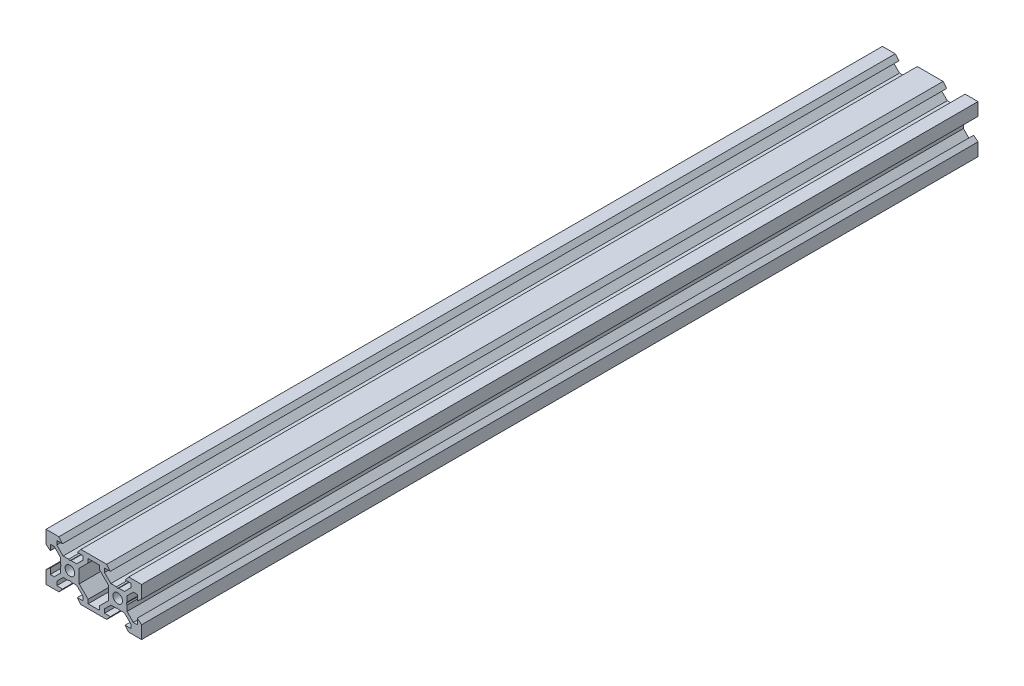
SolidWorks part; units mm, degrees
ref_plane "Front Plane" through (0, 0, 0) normal (0, 0, 1) x (1, 0, 0)
ref_plane "Top Plane" through (0, 0, 0) normal (0, 1, 0) x (1, 0, 0)
ref_plane "Right Plane" through (0, 0, 0) normal (1, 0, 0) x (0, 0, -1)
sketch "Sketch1" plane through (0, 0, 0) normal (0, 0, 1) x (1, 0, 0)
  line L0 (-5.3896, 10) -> (5.3896, 10)
  line L1 (0, 10) -> (0, 4.6104) construction
  line L2 (-6.1, -2.8393) -> (-2.3769, -6.5562)
  line L3 (5.3896, -10) -> (-5.3896, -10) construction
  line L5 (-6.1, 2.8393) -> (-6.1, -2.8393)
  line L6 (-4.5, 8.2) -> (-4.5, 6.5562)
  line L7 (2.3832, 6.5562) -> (2.3832, 8.2)
  line L9 (-6.1, 2.8393) -> (-2.3832, 6.5562)
  line L10 (-4.5, 6.5562) -> (-7.1607, 3.9)
  line L11 (-2.3832, 6.5562) -> (-2.3832, 8.2)
  line L12 (-5.3896, 10) -> (-6.9, 8.2)
  line L13 (6.1, 2.8393) -> (2.3832, 6.5562)
  line L14 (-6.9, 8.2) -> (-4.5, 8.2)
  line L15 (-16.5562, 5.5) -> (-18.2, 5.5)
  line L16 (0, 0) -> (6.1, 0) construction
  line L17 (-6.9, -8.2) -> (-4.5, -8.2)
  line L18 (-2.3769, -6.5562) -> (-2.3769, -8.2)
  line L19 (-5.3896, -10) -> (-6.9, -8.2)
  line L20 (2.3769, -6.5562) -> (2.3769, -8.2)
  line L21 (-9.4804, -3.9002) -> (-10, -3.6002)
  line L22 (-9.4804, 3.8998) -> (-10, 3.5998)
  line L23 (6.1, -2.8393) -> (2.3769, -6.5562)
  line L24 (-2.3769, -8.2) -> (2.3769, -8.2)
  line L25 (-2.3832, 8.2) -> (2.3832, 8.2)
  line L26 (-9.4804, 3.8998) -> (-7.1607, 3.9)
  line L27 (-5.3896, -10) -> (5.3896, -10)
  line L28 (-9.4804, -3.9002) -> (-7.1604, -3.9002)
  line L29 (-4.5, -6.5562) -> (-7.1607, -3.9)
  line L30 (-20, 10) -> (20, 10) construction
  line L32 (6.1, 2.8393) -> (6.1, -2.8393)
  line L33 (-4.5, -8.2) -> (-4.5, -6.5562)
  line L34 (-16.5562, -5.5) -> (-18.2, -5.5)
  line L36 (-10, 0) -> (-10, 8.2) construction
  line L37 (-20, -10) -> (-14.6104, -10) construction
  line L38 (-20, -10) -> (-20, -4.6104) construction
  line L39 (-20, 10) -> (-20, 4.6104) construction
  line L40 (-20, 10) -> (-14.6104, 10) construction
  line L41 (-20, -10) -> (-20, -4.6104)
  line L42 (-15.5, -8.2) -> (-15.5, -6.5562)
  line L43 (-20, -10) -> (-14.6104, -10)
  line L44 (7.1519, 3.8998) -> (9.4804, 3.8998)
  line L45 (-16.5562, -5.5) -> (-13.9, -2.8393)
  line L46 (-15.5, -6.5562) -> (-12.8393, -3.9)
  line L47 (-12.8393, -3.9) -> (-10.5196, -3.9002)
  line L48 (-13.9, -2.8393) -> (-13.9, -0.5196)
  line L49 (-12.8393, 3.9) -> (-10.5196, 3.8998)
  line L50 (-13.9, 0.5196) -> (-13.9, 2.8393)
  line L51 (-13.9, 0.5196) -> (-13.6, 0)
  line L52 (-13.6, 0) -> (-13.9, -0.5196)
  line L53 (-10.5196, 3.8998) -> (-10, 3.5998)
  line L54 (-10.5196, -3.9002) -> (-10, -3.6002)
  line L55 (-20, -4.6104) -> (-18.2, -3.1)
  line L56 (-14.6104, -10) -> (-13.1, -8.2)
  line L57 (-18.2, -3.1) -> (-18.2, -5.5)
  line L58 (-13.1, -8.2) -> (-15.5, -8.2)
  line L59 (-20, -10) -> (20, -10) construction
  line L60 (-20, -10) -> (-20, 10) construction
  line L61 (-13.1, 8.2) -> (-15.5, 8.2)
  line L62 (-18.2, 3.1) -> (-18.2, 5.5)
  line L63 (-14.6104, 10) -> (-13.1, 8.2)
  line L64 (-20, 4.6104) -> (-18.2, 3.1)
  line L65 (-15.5, 6.5562) -> (-12.8393, 3.9)
  line L66 (-16.5562, 5.5) -> (-13.9, 2.8393)
  line L67 (-20, 10) -> (-20, 4.6104)
  line L68 (-20, 10) -> (-14.6104, 10)
  line L69 (-15.5, 8.2) -> (-15.5, 6.5562)
  line L70 (4.5, 6.5562) -> (7.1519, 3.8998)
  line L71 (15.5, 6.5562) -> (12.8481, 3.8998)
  line L72 (0, -10) -> (0, 10) construction
  line L73 (-20, -10) -> (0, 10) construction
  line L74 (10.5196, 3.8998) -> (12.8481, 3.8998)
  line L75 (12.8393, -3.9) -> (10.5192, -3.9)
  line L76 (20, -10) -> (0, 10) construction
  line L77 (20, -10) -> (20, 10) construction
  line L78 (20, 10) -> (14.6104, 10) construction
  line L79 (20, 10) -> (20, 4.6104) construction
  line L80 (20, -10) -> (20, -4.6104) construction
  line L81 (20, -10) -> (14.6104, -10) construction
  line L82 (10, 0) -> (10, 8.2) construction
  line L83 (20, 10) -> (20, 4.6104)
  line L84 (15.5, 8.2) -> (15.5, 6.5562)
  line L85 (20, 10) -> (14.6104, 10)
  line L87 (16.5562, 5.5) -> (13.9, 2.8393)
  line L89 (20, 4.6104) -> (18.2, 3.1)
  line L90 (14.6104, 10) -> (13.1, 8.2)
  line L91 (18.2, 3.1) -> (18.2, 5.5)
  line L92 (13.1, 8.2) -> (15.5, 8.2)
  line L93 (13.1, -8.2) -> (15.5, -8.2)
  line L94 (18.2, -3.1) -> (18.2, -5.5)
  line L95 (14.6104, -10) -> (13.1, -8.2)
  line L96 (20, -4.6104) -> (18.2, -3.1)
  line L97 (10.5196, -3.9002) -> (10, -3.6002)
  line L98 (10.5196, 3.8998) -> (10, 3.5998)
  line L99 (13.6, 0) -> (13.9, -0.5196)
  line L100 (13.9, 0.5196) -> (13.6, 0)
  line L101 (13.9, 0.5196) -> (13.9, 2.8393)
  line L102 (9.4808, -3.9) -> (7.1607, -3.9)
  line L103 (13.9, -2.8393) -> (13.9, -0.5196)
  line L105 (15.5, -6.5562) -> (12.8393, -3.9)
  line L106 (16.5562, -5.5) -> (13.9, -2.8393)
  line L107 (20, -10) -> (20, -4.6104)
  line L108 (20, -10) -> (14.6104, -10)
  line L109 (15.5, -8.2) -> (15.5, -6.5562)
  line L111 (16.5562, -5.5) -> (18.2, -5.5)
  line L112 (4.5, -8.2) -> (4.5, -6.5562)
  line L114 (4.5, -6.5562) -> (7.1607, -3.9)
  line L121 (9.4804, 3.8998) -> (10, 3.5998)
  line L122 (9.4804, -3.9002) -> (10, -3.6002)
  line L124 (5.3896, -10) -> (6.9, -8.2)
  line L126 (6.9, -8.2) -> (4.5, -8.2)
  line L128 (16.5562, 5.5) -> (18.2, 5.5)
  line L129 (6.9, 8.2) -> (4.5, 8.2)
  line L131 (5.3896, 10) -> (6.9, 8.2)
  line L135 (4.5, 8.2) -> (4.5, 6.5562)
  circle A0 centre (-10, 0) radius 2
  circle A1 centre (10, 0) radius 2
  dimension "D14" = 4
  dimension "D1" = 20
  dimension "D2" = 5.3896
  dimension "D3" = 1.8
  dimension "D4" = 1.5104
  dimension "D5" = 4.5
  dimension "D6" = 5.5
  dimension "D7" = 120
  dimension "D8" = 0.3
  dimension "D9" = 2.3197
  dimension "D10" = 7.8
  dimension "D11" = 20
  dimension "D12" = 1.5
  dimension "D13" = 2.6607
  dimension "D15" = 50
  dimension "D16" = 1.5
  dimension "D17" = 1.8
  dimension "D18" = 16.4
  dimension "D19" = 2.3832
  dimension "D20" = 45
extrude "Boss-Extrude1" add sketch "Sketch1" along normal blind 350
